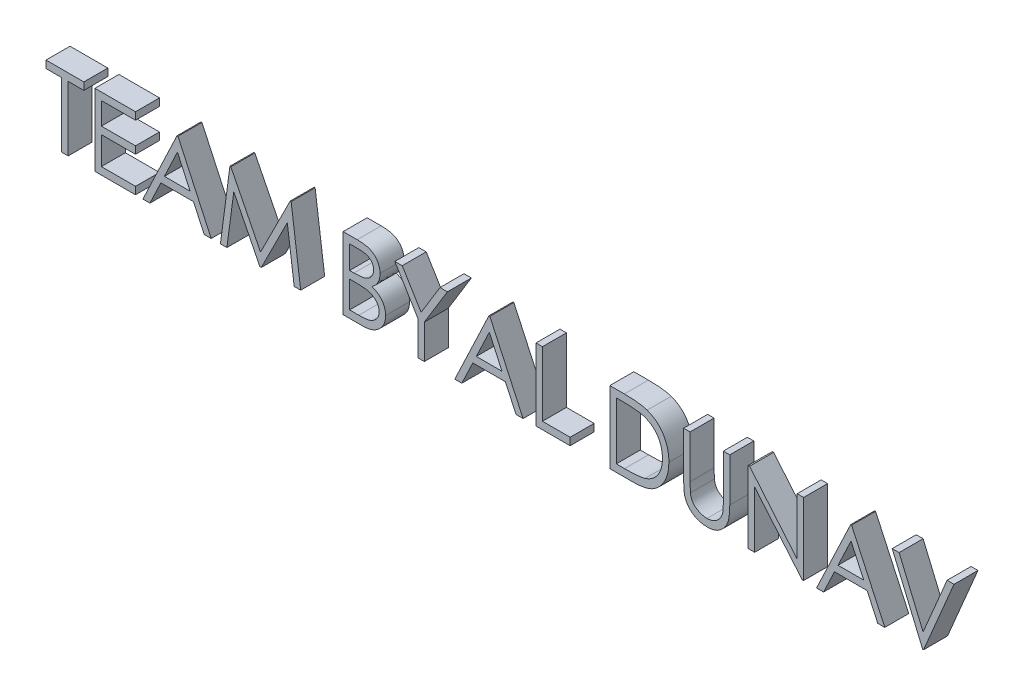
SolidWorks part; units mm, degrees
ref_plane "Front Plane" through (0, 0, 0) normal (0, 0, 1) x (1, 0, 0)
ref_plane "Top Plane" through (0, 0, 0) normal (0, 1, 0) x (1, 0, 0)
ref_plane "Right Plane" through (0, 0, 0) normal (1, 0, 0) x (0, 0, -1)
sketch "Sketch1" plane through (0, 0, 0) normal (0, 0, 1) x (1, 0, 0)
  line L0 (-240, 0) -> (240, 0) construction
  line L5 (120, -25) -> (0, 0) construction
  line L6 (222.7317, 46.4024) -> (-120, -25) construction
  line L7 (-120, -25) -> (240, -25) construction
  text T0 "TEAM BYAL DUNAV" font "Century Gothic" height 30
  point P0 (0, 0)
  dimension "D3" = 25
extrude "Boss-Extrude1" add sketch "Sketch1" along normal blind 10
